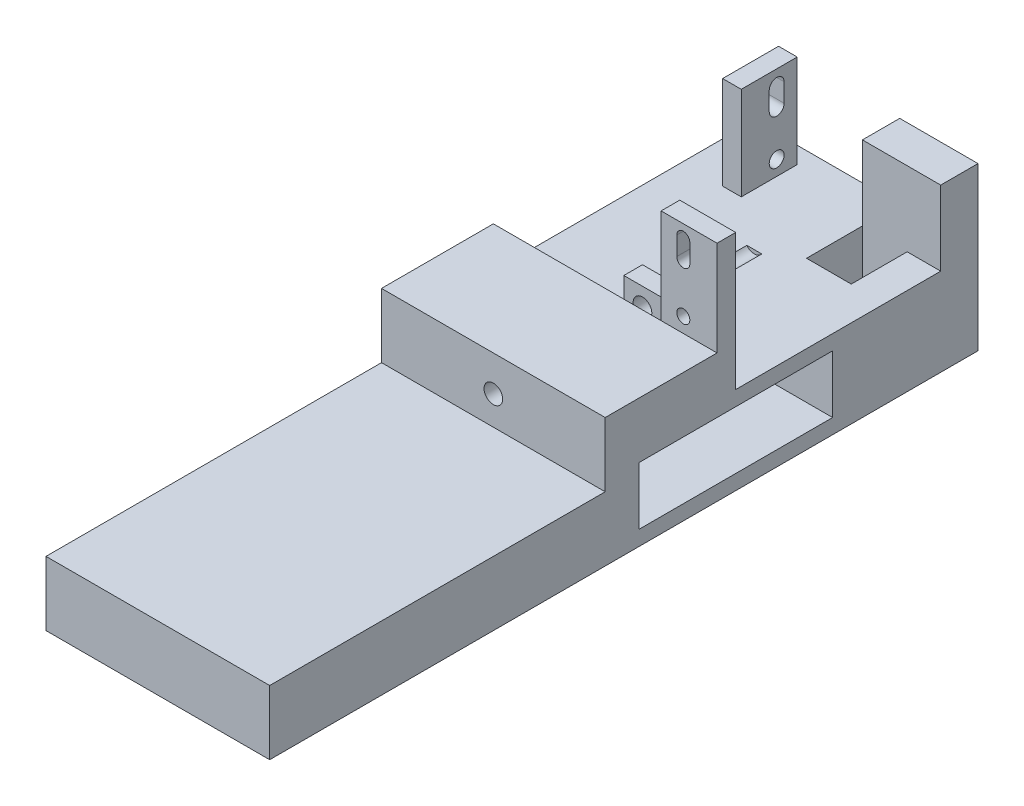
SolidWorks part; units mm, degrees
ref_plane "Front Plane" through (0, 0, 0) normal (0, 0, 1) x (1, 0, 0)
ref_plane "Top Plane" through (0, 0, 0) normal (0, 1, 0) x (1, 0, 0)
ref_plane "Right Plane" through (0, 0, 0) normal (1, 0, 0) x (0, 0, -1)
sketch "Sketch1" plane through (0, 0, 0) normal (0, 1, 0) x (1, 0, 0)
  line L1 (0, 0) -> (-60, 0)
  line L2 (0, 0) -> (0, 70)
  line L3 (0, 70) -> (-60, 70)
  line L4 (-60, 0) -> (-60, 70)
  dimension "D1" = 60
  dimension "D2" = 70
extrude "Boss-Extrude1" add sketch "Sketch1" along normal blind 23.5
shell "Shell1" thickness 9
sketch "Sketch2" plane through (0, 23.5, 0) normal (0, 1, 0) x (1, 0, 0)
  line L0 (-30, 40) -> (-30, 30) construction
  line L1 (-25, 45) -> (-35, 45)
  line L2 (-25, 45) -> (-25, 40)
  line L3 (-25, 40) -> (-35, 40)
  line L4 (-35, 45) -> (-35, 40)
  line L5 (-35, 30) -> (-25, 30)
  line L6 (-35, 30) -> (-35, 25)
  line L7 (-35, 25) -> (-25, 25)
  line L8 (-25, 30) -> (-25, 25)
  line L9 (-60, 70) -> (-60, 0) construction
  line L10 (0, 70) -> (-60, 70) construction
  point P12 (-30, 35)
  point P13 (-30, 70)
  point P16 (-60, 35)
  dimension "D1" = 5
  dimension "D2" = 10
  dimension "D3" = 10
extrude "Boss-Extrude2" add sketch "Sketch2" along normal blind 6.5
sketch "Sketch5" plane through (0, 23.5, 0) normal (0, 1, 0) x (1, 0, 0)
  line L0 (-60, 70) -> (-60, 0) construction
  line L1 (-60, 30) -> (0, 30)
  line L2 (-60, 30) -> (-60, 0)
  line L3 (-60, 0) -> (0, 0)
  line L4 (0, 30) -> (0, 0)
  line L5 (-25, 30) -> (-35, 30) construction
extrude "Boss-Extrude3" add sketch "Sketch5" along normal blind 11
sketch "Sketch3" plane through (0, 0, -45) normal (0, 0, -1) x (-1, 0, 0)
  line L0 (25, 30) -> (35, 30) construction
  circle A0 centre (30, 25) radius 2.5
  point P4 (30, 30)
  dimension "D1" = 5
  dimension "D2" = 5
extrude "Cut-Extrude1" cut sketch "Sketch3" against normal through all both and the other way through all
sketch "Sketch4" plane through (0, 23.5, 0) normal (0, 1, 0) x (1, 0, 0)
  line L0 (-35, 40) -> (-25, 40) construction
  line L1 (-15, 30) -> (-45, 30)
  line L2 (-15, 30) -> (-15, 40)
  line L3 (-15, 40) -> (-45, 40)
  line L4 (-45, 30) -> (-45, 40)
  line L6 (-25, 45) -> (-35, 45) construction
  point P10 (-30, 45)
  dimension "D1" = 30
  dimension "D2" = 15
  dimension "D3" = 10
extrude "Cut-Extrude2" cut sketch "Sketch4" against normal blind 10
sketch "Sketch6" plane through (0, 23.5, 0) normal (0, 1, 0) x (1, 0, 0)
  line L0 (0, 30) -> (-15, 30) construction
  line L1 (-15, 30) -> (0, 30)
  line L2 (-15, 30) -> (-15, 35)
  line L3 (-15, 35) -> (0, 35)
  line L4 (0, 30) -> (0, 35)
  line L5 (0, 30) -> (0, 70) construction
  dimension "D1" = 5
extrude "Boss-Extrude4" add sketch "Sketch6" along normal blind 36.5
sketch "Sketch8" plane through (0, 0, -35) normal (0, 0, -1) x (-1, 0, 0)
  line L0 (7.3, 56.5) -> (7.3, 51.5)
  line L1 (0, 23.5) -> (15, 23.5) construction
  line L2 (15, 60) -> (15, 23.5) construction
  line L3 (10.8, 56.5) -> (10.8, 51.5)
  arc A0 (10.8, 56.5) -> (7.3, 56.5) centre (9.05, 56.5) ccw
  circle A1 centre (9.05, 38.5) radius 1.75
  arc A2 (7.3, 51.5) -> (10.8, 51.5) centre (9.05, 51.5) ccw
  dimension "D1" = 3.5
  dimension "D2" = 15
  dimension "D3" = 18
  dimension "D4" = 5.95
  dimension "D5" = 5
extrude "Cut-Extrude3" cut sketch "Sketch8" against normal blind 10
sketch "Sketch9" plane through (0, 0, -70) normal (0, 0, -1) x (-1, 0, 0)
  line L1 (0, 23.5) -> (60, 23.5)
  line L2 (0, 23.5) -> (0, 0)
  line L3 (0, 0) -> (60, 0)
  line L4 (60, 23.5) -> (60, 0)
extrude "Boss-Extrude5" add sketch "Sketch9" along normal blind 30
sketch "Sketch10" plane through (0, 0, -100) normal (0, 0, -1) x (-1, 0, 0)
  line L0 (60, 23.5) -> (0, 23.5) construction
  line L1 (30, 23.5) -> (0, 23.5)
  line L2 (30, 23.5) -> (30, 0)
  line L3 (30, 0) -> (0, 0)
  line L4 (0, 23.5) -> (0, 0)
sketch "Sketch11" plane through (0, 23.5, 0) normal (0, 1, 0) x (1, 0, 0)
  line L7 (0, 35) -> (0, 100) construction
  line L8 (-9, 90) -> (-21, 90)
  line L9 (-9, 90) -> (-9, 75)
  line L10 (-9, 75) -> (-21, 75)
  line L11 (-21, 90) -> (-21, 75)
  line L12 (-30, 100) -> (0, 100) construction
  dimension "D1" = 15
  dimension "D2" = 9
  dimension "D3" = 10
  dimension "D4" = 12
extrude "Cut-Extrude4" cut sketch "Sketch11" against normal through all both and the other way through all
sketch "Sketch12" plane through (0, 23.5, 0) normal (0, 1, 0) x (1, 0, 0)
  line L1 (-44, 95.5) -> (-49, 95.5)
  line L2 (-44, 95.5) -> (-44, 80.5)
  line L3 (-44, 80.5) -> (-49, 80.5)
  line L4 (-49, 95.5) -> (-49, 80.5)
  dimension "D1" = 5
  dimension "D2" = 15
extrude "Boss-Extrude7" add sketch "Sketch12" along normal blind 25
sketch "Sketch13" plane through (-49, 0, 0) normal (-1, 0, 0) x (0, 0, 1)
  line L0 (-90, 44.5) -> (-90, 39.5) construction
  line L1 (-88, 44.5) -> (-88, 39.5)
  line L2 (-92, 44.5) -> (-92, 39.5)
  circle A2 centre (-90, 27.5) radius 1.5 construction
  circle A3 centre (-90, 42) radius 1.5 construction
  circle A4 centre (-90, 27.5) radius 1.5
  circle A5 centre (-90, 42) radius 1.5
  circle A6 centre (-90, 27.5) radius 2
  circle A7 centre (-90, 42) radius 2
  arc A8 (-88, 44.5) -> (-92, 44.5) centre (-90, 44.5) ccw
  arc A9 (-92, 39.5) -> (-88, 39.5) centre (-90, 39.5) ccw
  point P12 (-90, 42)
  dimension "D2" = 5
  dimension "D1" = 0.5
extrude "Cut-Extrude5" cut sketch "Sketch13" against normal blind 25 contours A6 | A8 L2 A9 L1
sketch "Sketch14" plane through (0, 23.5, 0) normal (0, 1, 0) x (1, 0, 0)
  line L1 (0, 100) -> (-21, 100)
  line L2 (0, 100) -> (0, 90)
  line L3 (0, 90) -> (-21, 90)
  line L4 (-21, 100) -> (-21, 90)
  line L5 (-21, 90) -> (-21, 75) construction
  dimension "D1" = 10
extrude "Boss-Extrude8" add sketch "Sketch14" along normal blind 20
sketch "Sketch15" plane through (0, 0, 0) normal (0, 0, 1) x (1, 0, 0)
  line L0 (0, 34.5) -> (0, 0) construction
  line L1 (-60, 0) -> (0, 0)
  line L2 (-60, 0) -> (-60, 17.25)
  line L3 (-60, 17.25) -> (0, 17.25)
  line L4 (0, 0) -> (0, 17.25)
extrude "Boss-Extrude9" add sketch "Sketch15" along normal blind 90
sketch "Sketch16" plane through (0, 0, 0) normal (1, 0, 0) x (0, 0, -1)
  line L0 (0, 34.5) -> (0, 17.25) construction
  line L1 (61, 4) -> (9, 4)
  line L2 (61, 4) -> (61, 19.5)
  line L3 (61, 19.5) -> (9, 19.5)
  line L4 (9, 4) -> (9, 19.5)
  line L5 (100, 23.5) -> (100, 0) construction
  line L6 (35, 23.5) -> (90, 23.5) construction
  line L7 (-90, 0) -> (100, 0) construction
  dimension "D1" = 9
  dimension "D2" = 39
  dimension "D3" = 4
  dimension "D4" = 4
extrude "Cut-Extrude6" cut sketch "Sketch16" against normal through all both and the other way through all
equation "\"7ץ5\"=5"
